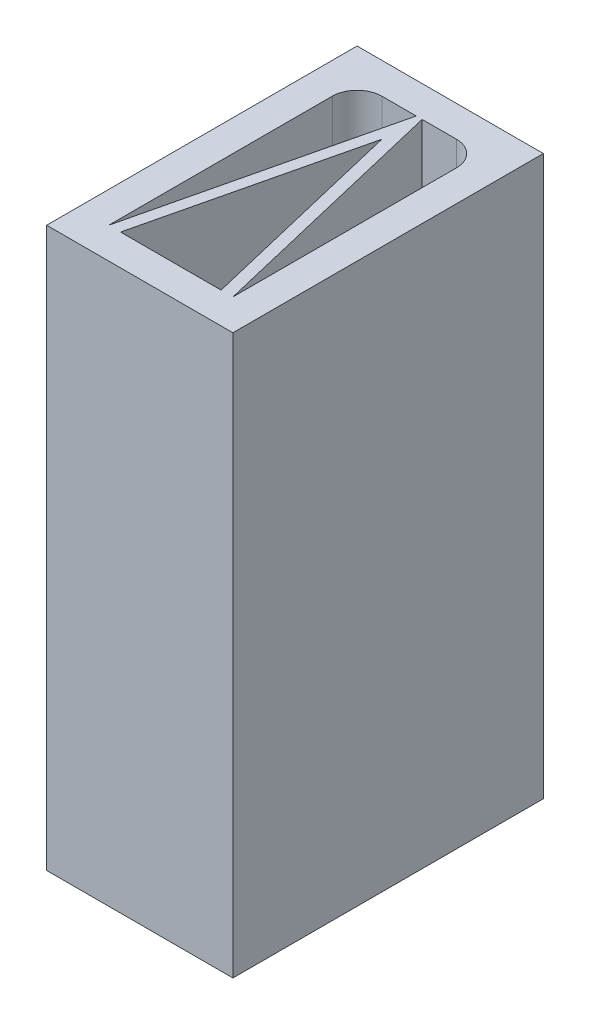
SolidWorks part; units mm, degrees
ref_plane "Front Plane" through (0, 0, 0) normal (0, 0, 1) x (1, 0, 0)
ref_plane "Top Plane" through (0, 0, 0) normal (0, 1, 0) x (1, 0, 0)
ref_plane "Right Plane" through (0, 0, 0) normal (1, 0, 0) x (0, 0, -1)
sketch "Sketch1" plane through (0, 0, 0) normal (0, 1, 0) x (1, 0, 0)
  line L0 (7.5, 25) -> (7.5, 22.5) construction
  line L1 (0, 0) -> (15, 0)
  line L2 (0, 0) -> (0, 25)
  line L3 (0, 25) -> (15, 25)
  line L4 (15, 0) -> (15, 25)
  line L5 (2.5, 22.5) -> (12.5, 22.5)
  line L6 (2.5, 22.5) -> (2.5, 2.5)
  line L7 (2.5, 2.5) -> (12.5, 2.5)
  line L8 (12.5, 22.5) -> (12.5, 2.5)
  line L9 (0, 12.5) -> (2.5, 12.5) construction
  dimension "D1" = 15
  dimension "D2" = 25
  dimension "D3" = 2.5
  dimension "D4" = 2.5
extrude "Boss-Extrude1" add sketch "Sketch1" along normal blind 45
sketch "Sketch3" plane through (0, 0, 0) normal (0, -1, 0) x (1, 0, 0)
  line L0 (12.5, -2.5) -> (7.5, -23.5)
  line L2 (7.5, -23.5) -> (2.5, -2.5)
  line L3 (7.5, -23.5) -> (7.5, -2.5) construction
  line L4 (2.5, -2.5) -> (12.5, -2.5) construction
  line L5 (12.5, -2.5) -> (11.5476, -2.5)
  line L6 (11.5476, -2.5) -> (7.5, -19.5)
  line L7 (7.5, -19.5) -> (3.4524, -2.5)
  line L8 (3.4524, -2.5) -> (2.5, -2.5)
  line L9 (12.5, -22.5) -> (2.5, -22.5) construction
  dimension "D1" = 4
  dimension "D2" = 1
extrude "Boss-Extrude4" add sketch "Sketch3" against normal through all
fillet "Fillet2" radius 2 2 edges at (2.5, 22.5, -22.5) (12.5, 22.5, -22.5)
